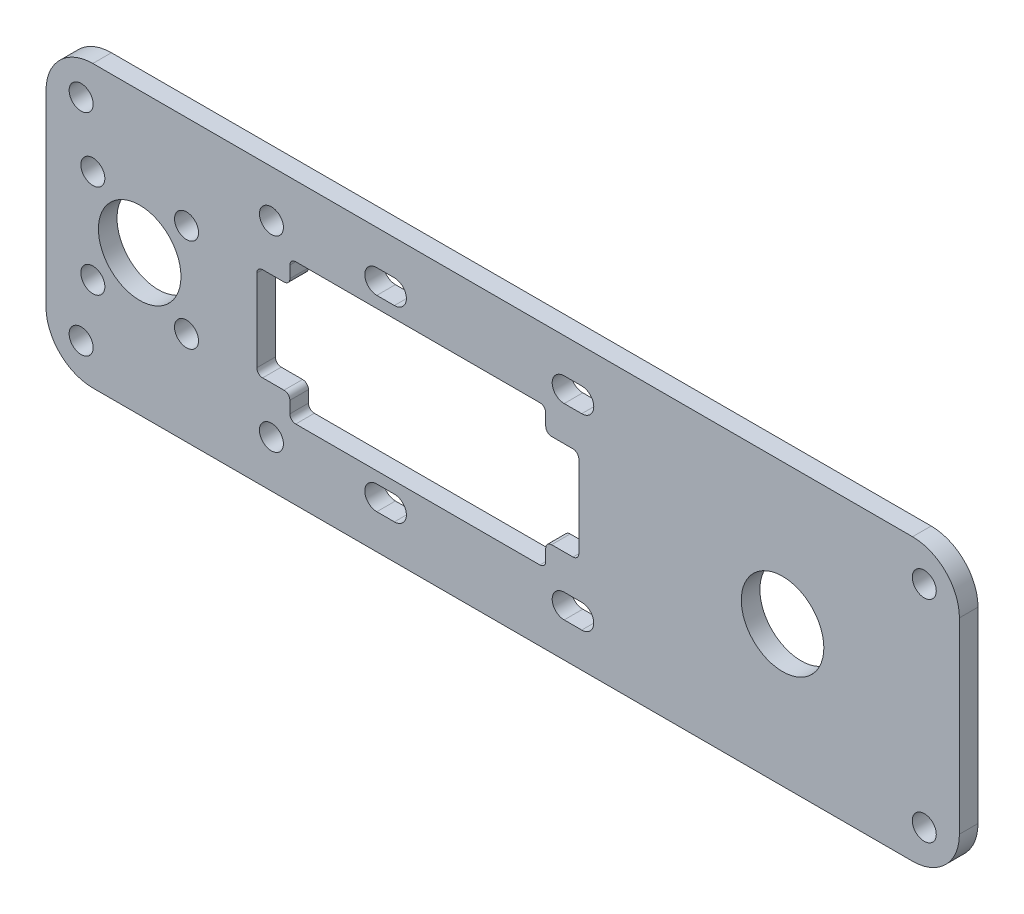
SolidWorks part; units mm, degrees
ref_plane "Front Plane" through (0, 0, 0) normal (0, 0, 1) x (1, 0, 0)
ref_plane "Top Plane" through (0, 0, 0) normal (0, 1, 0) x (1, 0, 0)
ref_plane "Right Plane" through (0, 0, 0) normal (1, 0, 0) x (0, 0, -1)
sketch "Sketch2" plane through (0, 0, 0) normal (0, 0, 1) x (1, 0, 0)
  line L0 (0, 0) -> (0, -72030.4166) construction
  line L1 (78, 24) -> (-78, 24)
  line L2 (78, 24) -> (78, -24)
  line L3 (78, -24) -> (-78, -24)
  line L4 (-78, 24) -> (-78, -24)
  line L5 (78, 24) -> (-78, -24) construction
  line L6 (78, -24) -> (-78, 24) construction
  line L7 (0, 0) -> (72030.4166, 0) construction
  line L9 (-46, 20) -> (17, 20) construction
  line L10 (-46, 20) -> (-46, -20) construction
  line L11 (-46, -20) -> (17, -20) construction
  line L12 (17, 20) -> (17, -20) construction
  line L13 (-46, 20) -> (17, -20) construction
  line L14 (-46, -20) -> (17, 20) construction
  line L15 (-70, 8) -> (-54, 8) construction
  line L16 (-70, 8) -> (-70, -8) construction
  line L17 (-70, -8) -> (-54, -8) construction
  line L18 (-54, 8) -> (-54, -8) construction
  line L19 (-70, 8) -> (-54, -8) construction
  line L20 (-70, -8) -> (-54, 8) construction
  line L21 (10.5, -16) -> (-39.5, -16) construction
  line L22 (10.5, -16) -> (10.5, 16) construction
  line L23 (10.5, 16) -> (-39.5, 16) construction
  line L24 (-39.5, -16) -> (-39.5, 16) construction
  line L25 (10.5, -16) -> (-39.5, 16) construction
  line L26 (10.5, 16) -> (-39.5, -16) construction
  line L31 (7.35, -12) -> (-36.35, -12)
  line L32 (7.35, -12) -> (7.35, -8)
  line L33 (-50, -12) -> (-74, -12) construction
  line L34 (-50, -12) -> (-50, 12) construction
  line L35 (-50, 12) -> (-74, 12) construction
  line L36 (-74, -12) -> (-74, 12) construction
  line L37 (-50, -12) -> (-74, 12) construction
  line L38 (-50, 12) -> (-74, -12) construction
  line L39 (7.35, 12) -> (-36.35, 12)
  line L40 (-36.35, -12) -> (-36.35, -8)
  line L41 (7.35, -12) -> (-36.35, 12) construction
  line L42 (7.35, 12) -> (-36.35, -12) construction
  line L44 (-4.7, 19.1) -> (47.7956, 19.1) construction
  line L45 (5.35, -10) -> (-34.35, -10) construction
  line L46 (5.35, -10) -> (5.35, 10) construction
  line L47 (5.35, 10) -> (-34.35, 10) construction
  line L48 (-34.35, -10) -> (-34.35, 10) construction
  line L49 (5.35, -10) -> (-34.35, 10)
  line L50 (5.35, 10) -> (-34.35, -10)
  line L51 (-4.7, -19.1) -> (47.7956, -19.1) construction
  line L52 (-36.35, 8) -> (-42, 8)
  line L53 (13, -8) -> (7.35, -8)
  line L54 (13, -8) -> (13, 8)
  line L55 (13, 8) -> (7.35, 8)
  line L56 (-42, -8) -> (-42, 8)
  line L57 (13, -8) -> (-42, 8) construction
  line L58 (13, 8) -> (-42, -8) construction
  line L59 (-36.35, -8) -> (-42, -8)
  line L60 (-36.35, 8) -> (-36.35, 12)
  line L61 (7.35, 8) -> (7.35, 12)
  line L62 (5.35, 8) -> (-30.38, 8)
  line L63 (5.35, -8) -> (-34.35, -8)
  line L64 (9.0311, 16) -> (-48518.2868, 16) construction
  line L65 (10.5, 18.05) -> (13.5, 18.05)
  line L66 (10.5, 13.95) -> (13.5, 13.95)
  line L67 (-21.5, 13.95) -> (-18.5, 13.95)
  line L68 (-21.5, 18.05) -> (-18.5, 18.05)
  line L69 (10.5, 13.95) -> (-21.5, 13.95) construction
  line L70 (-21.5, -18.05) -> (-18.5, -18.05)
  line L71 (-21.5, -13.95) -> (-18.5, -13.95)
  line L72 (10.5, -18.05) -> (13.5, -18.05)
  line L73 (10.5, -13.95) -> (13.5, -13.95)
  line L75 (72, -18) -> (-72, -18) construction
  line L76 (72, -18) -> (72, 18) construction
  line L77 (72, 18) -> (-72, 18) construction
  line L78 (-72, -18) -> (-72, 18) construction
  line L79 (72, -18) -> (-72, 18) construction
  line L80 (72, 18) -> (-72, -18) construction
  circle A0 centre (-70, 8) radius 2.05
  circle A1 centre (-54, 8) radius 2.05
  circle A2 centre (-54, -8) radius 2.05
  circle A3 centre (-70, -8) radius 2.05
  arc A6 (10.5, 18.05) -> (10.5, 13.95) centre (10.5, 16) ccw
  circle A7 centre (-39.5, 16) radius 2.05
  circle A8 centre (-39.5, -16) radius 2.05
  circle A9 centre (-4.7, 0) radius 19.1 construction
  arc A12 (-4.7, 19.1) -> (-4.7, -19.1) centre (-4.7, 0) ccw construction
  circle A13 centre (47.7956, 0) radius 19.1 construction
  arc A14 (47.7956, -19.1) -> (47.7956, 19.1) centre (47.7956, 0) ccw construction
  arc A15 (-4.7, 19.1) -> (-4.7, -19.1) centre (-4.7, 0) ccw construction
  circle A16 centre (47.7956, 0) radius 7.05
  arc A18 (13.5, 13.95) -> (13.5, 18.05) centre (13.5, 16) ccw
  arc A19 (-18.5, 13.95) -> (-18.5, 18.05) centre (-18.5, 16) ccw
  arc A20 (-21.5, 18.05) -> (-21.5, 13.95) centre (-21.5, 16) ccw
  arc A21 (-21.5, -18.05) -> (-21.5, -13.95) centre (-21.5, -16) cw
  arc A22 (-18.5, -13.95) -> (-18.5, -18.05) centre (-18.5, -16) cw
  arc A23 (10.5, -18.05) -> (10.5, -13.95) centre (10.5, -16) cw
  arc A24 (13.5, -13.95) -> (13.5, -18.05) centre (13.5, -16) cw
  circle A25 centre (-62, 0) radius 7.05
  circle A26 centre (72, 18) radius 2.05
  circle A27 centre (72, -18) radius 2.05
  circle A28 centre (-72, -18) radius 2.05
  circle A29 centre (-72, 18) radius 2.05
  point P0 (0, 0)
  point P10 (-14.5, 0)
  point P15 (-62, 0)
  point P20 (-14.5, 0)
  point P25 (-14.5, 0)
  point P30 (-62, 0)
  point P39 (-14.5, 0)
  point P47 (-14.5, 0)
  point P52 (-14.5, 0)
  point P95 (0, 0)
  dimension "D7" = 4.1
  dimension "D14" = 38.2
  dimension "D21" = 14.1
  dimension "D1" = 156
  dimension "D2" = 48
  dimension "D3" = 63
  dimension "D4" = 40
  dimension "D5" = 50
  dimension "D6" = 32
  dimension "D8" = 16
  dimension "D9" = 16
  dimension "D10" = 24
  dimension "D11" = 24
  dimension "D12" = 43.7
  dimension "D13" = 24
  dimension "D16" = 39.7
  dimension "D17" = 20
  dimension "D18" = 10.05
  dimension "D19" = 4
  dimension "D20" = 8
  dimension "D22" = 55
  dimension "D23" = 16
  dimension "D24" = 3
  dimension "D26" = 32
  dimension "D27" = 144
  dimension "D28" = 36
  dimension "D25" = 2
extrude "Boss-Extrude2" add sketch "Sketch2" along normal blind 3.175
fillet "Fillet1" radius 8 4 edges at (78, -24, 1.5875) (78, 24, 1.5875) (-78, -24, 1.5875) (-78, 24, 1.5875)
fillet "Fillet2" radius 1 12 edges at (7.35, -12, 1.5875) (7.35, -8, 1.5875) (13, -8, 1.5875) (7.35, 12, 1.5875) (7.35, 8, 1.5875) (13, 8, 1.5875) (-36.35, -12, 1.5875) (-42, -8, 1.5875) (-36.35, -8, 1.5875) (-42, 8, 1.5875) (-36.35, 8, 1.5875) (-36.35, 12, 1.5875)
equation "\"w\"= 156mm"
equation "\"h\" = 48mm"
equation "\"servoheight\"= 40mm"
equation "\"servowidth\"= 63mm"
equation "\"servowidthholes\" = 50mm"
equation "\"servoheightholes\"= 32mm"
equation "\"sh\"= 4.1mm"
equation "\"clampHoleSquare\"= 16mm"
equation "\"clampSquare\"= 24mm"
equation "\"D1@Sketch2\"=\"w\""
equation "\"D2@Sketch2\"=\"h\""
equation "\"D3@Sketch2\"=\"servowidth\""
equation "\"D4@Sketch2\"=\"servoheight\""
equation "\"D5@Sketch2\"=\"servowidthholes\""
equation "\"D6@Sketch2\"=\"servoheightholes\""
equation "\"D8@Sketch2\"=\"clampHoleSquare\""
equation "\"D9@Sketch2\"=\"clampHoleSquare\""
equation "\"D10@Sketch2\"=\"clampSquare\""
equation "\"D11@Sketch2\"=\"clampSquare\""
equation "\"D7@Sketch2\"=\"sh\""
equation "\"servoh\"= 20mm"
equation "\"servow\"= 39.7mm"
equation "\"D12@Sketch2\"=\"servow\"+4"
equation "\"D13@Sketch2\"=\"servoh\" +4"
equation "\"pitchDiameter\"= 38.2mm"
equation "\"D14@Sketch2\"=\"pitchDiameter\""
equation "\"D16@Sketch2\"=\"servow\""
equation "\"D17@Sketch2\"=\"servoh\""
equation "\"D18@Sketch2\"=10.05mm"
equation "\"pathLength\" = 225mm"
equation "\"D15@Sketch2\"=\"pathLength\""
equation "\"bearingOD\"= 14.1mm"
equation "\"D21@Sketch2\"=\"bearingOD\""
equation "\"thick\"= 3.175mm"
equation "\"D1@Boss-Extrude2\"=\"thick\""
equation "\"D27@Sketch2\"=\"w\"-12"
equation "\"D28@Sketch2\"=\"h\"-12"
